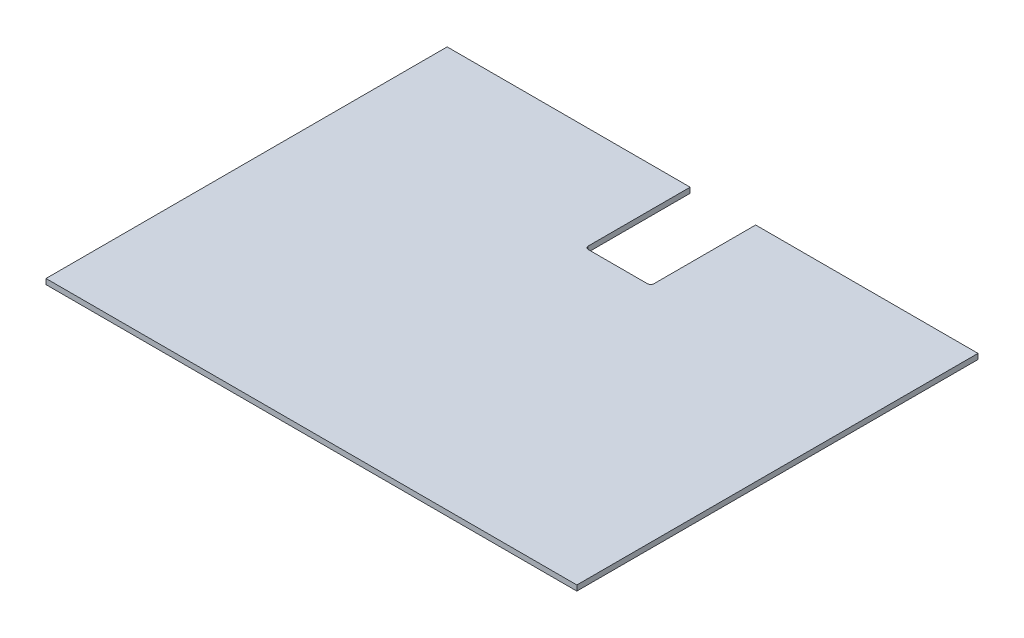
SolidWorks part; units mm, degrees
ref_plane "Front Plane" through (0, 0, 0) normal (0, 0, 1) x (1, 0, 0)
ref_plane "Top Plane" through (0, 0, 0) normal (0, 1, 0) x (1, 0, 0)
ref_plane "Right Plane" through (0, 0, 0) normal (1, 0, 0) x (0, 0, -1)
sketch "草图1" plane through (0, 0, 0) normal (0, 0, 1) x (1, 0, 0)
  line L1 (27.5504, 16) -> (821.5504, 16)
  line L2 (27.5504, 16) -> (27.5504, 24)
  line L3 (27.5504, 24) -> (821.5504, 24)
  line L4 (821.5504, 16) -> (821.5504, 24)
  line L5 (751.9496, 15.5) -> (750, 15.5) construction
  line L6 (26.5504, 14.5) -> (26.5504, 25.5) construction
  dimension "D1" = 794
  dimension "D2" = 8
  dimension "D3" = 0.5
  dimension "D4" = 1
extrude "凸台-拉伸1" add sketch "草图1" against normal blind 600
sketch "草图2" plane through (0, 16, 0) normal (0, -1, 0) x (1, 0, 0)
  line L0 (0, -603) -> (850, -603) construction
  line L1 (396, -443) -> (484, -443)
  line L2 (391, -448) -> (391, -603)
  line L3 (391, -603) -> (489, -603)
  line L4 (489, -448) -> (489, -603)
  line L8 (27.5504, -600) -> (27.5504, 0) construction
  arc A0 (484, -443) -> (489, -448) centre (484, -448) cw
  arc A1 (396, -443) -> (391, -448) centre (396, -448) ccw
  point P12 (489, -443)
  dimension "D4" = 5
  dimension "D1" = 363.4496
  dimension "D2" = 160
  dimension "D3" = 98
extrude "切除-拉伸1" cut sketch "草图2" against normal through all
